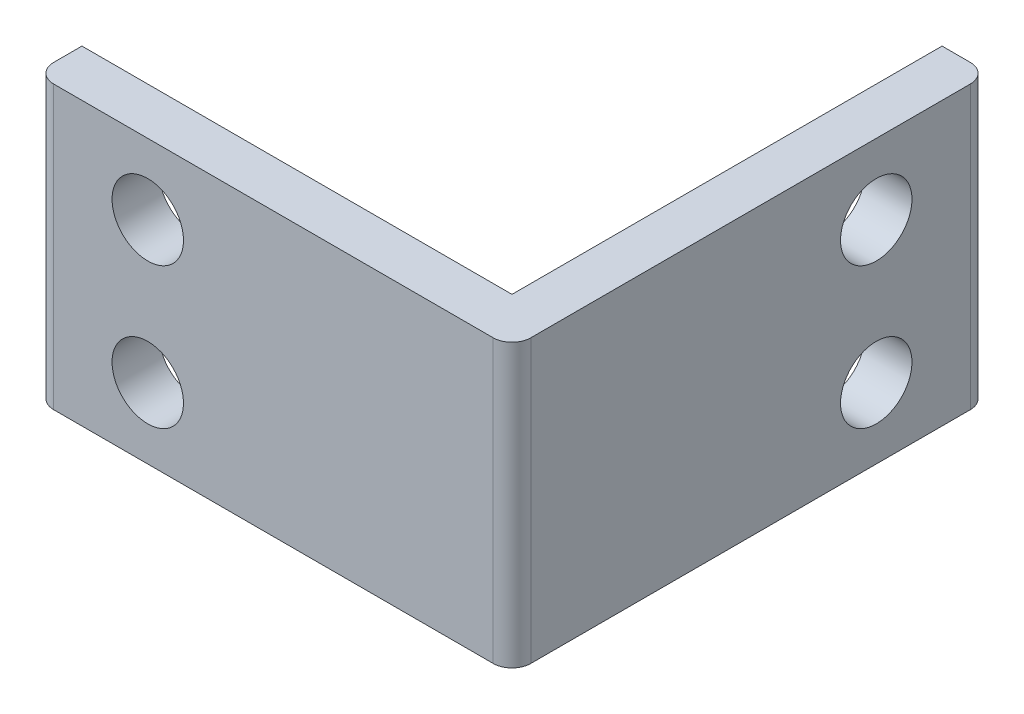
SolidWorks part; units mm, degrees
material "PBT General Purpose"
ref_plane "Front Plane" through (0, 0, 0) normal (0, 0, 1) x (1, 0, 0)
ref_plane "Top Plane" through (0, 0, 0) normal (0, 1, 0) x (1, 0, 0)
ref_plane "Right Plane" through (0, 0, 0) normal (1, 0, 0) x (0, 0, -1)
sketch "Sketch1" plane through (0, 0, 0) normal (0, 0, 1) x (1, 0, 0)
  line L1 (0, 0) -> (64.4398, 0)
  line L2 (0, 0) -> (0, 38.1)
  line L3 (0, 38.1) -> (64.4398, 38.1)
  line L4 (64.4398, 0) -> (64.4398, 38.1)
  dimension "D1" = 64.4398
  dimension "D2" = 38.1
extrude "Boss-Extrude1" add sketch "Sketch1" against normal blind 6.35
sketch "Sketch2" plane through (64.4398, 0, 0) normal (1, 0, 0) x (0, 0, -1)
  line L1 (0, 0) -> (64.4398, 0)
  line L2 (0, 0) -> (0, 38.1)
  line L3 (0, 38.1) -> (64.4398, 38.1)
  line L4 (64.4398, 0) -> (64.4398, 38.1)
  dimension "D1" = 64.4398
  dimension "D2" = 38.1
extrude "Boss-Extrude2" add sketch "Sketch2" against normal blind 6.35
sketch "Sketch3" plane through (64.4398, 0, 0) normal (1, 0, 0) x (0, 0, -1)
  line L0 (-7.7679, 19.05) -> (80.5504, 19.05) construction
  line L1 (64.4398, 38.1) -> (0, 38.1) construction
  line L2 (64.4398, 0) -> (64.4398, 38.1) construction
  circle A0 centre (49.1998, 28.575) radius 4.826
  circle A1 centre (49.1998, 9.525) radius 4.826
  dimension "D1" = 9.525
  dimension "D3" = 9.652
  dimension "D2" = 15.24
extrude "Cut-Extrude1" cut sketch "Sketch3" against normal through all
sketch "Sketch4" plane through (0, 0, 0) normal (0, 0, 1) x (1, 0, 0)
  line L0 (-1.295, 19.05) -> (77.1702, 19.05) construction
  circle A0 centre (15.24, 28.575) radius 4.826
  circle A1 centre (15.24, 9.525) radius 4.826
  dimension "D1" = 9.525
  dimension "D2" = 9.652
extrude "Cut-Extrude4" cut sketch "Sketch4" against normal through all
fillet "Fillet1" radius 2.54 1 edges at (0, 19.05, 0)
fillet "Fillet2" radius 2.54 1 edges at (64.4398, 19.05, -64.4398)
fillet "Fillet3" radius 2.54 1 edges at (64.4398, 19.05, 0)
